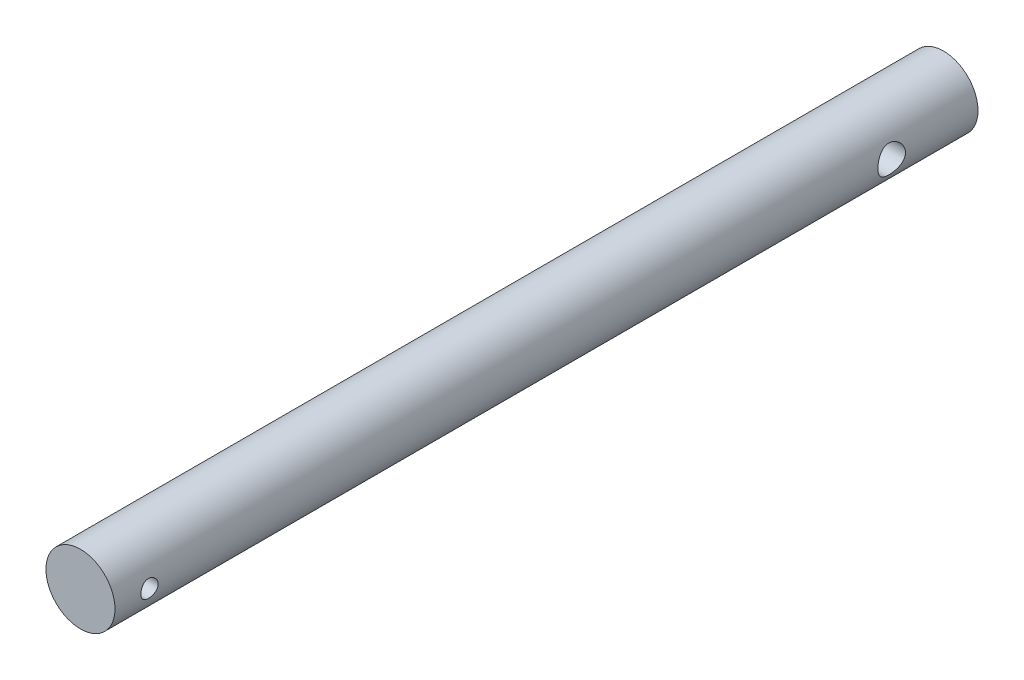
SolidWorks part; units mm, degrees
ref_plane "Front Plane" through (0, 0, 0) normal (0, 0, 1) x (1, 0, 0)
ref_plane "Top Plane" through (0, 0, 0) normal (0, 1, 0) x (1, 0, 0)
ref_plane "Right Plane" through (0, 0, 0) normal (1, 0, 0) x (0, 0, -1)
sketch "Sketch1" plane through (0, 0, 0) normal (0, 0, 1) x (1, 0, 0)
  circle A0 centre (0, 0) radius 10
  dimension "D1" = 20
extrude "Boss-Extrude1" add sketch "Sketch1" along normal blind 250
sketch "Sketch2" plane through (0, 0, 0) normal (1, 0, 0) x (0, 0, -1)
  line L0 (-250, 10) -> (-250, -10) construction
  circle A0 centre (-25, 0) radius 4
  circle A1 centre (-240, 0) radius 2.5
  dimension "D1" = 8
  dimension "D3" = 5
  dimension "D2" = 25
  dimension "D4" = 10
extrude "Cut-Extrude1" cut sketch "Sketch2" against normal through all both and the other way through all contours A1 | A0
